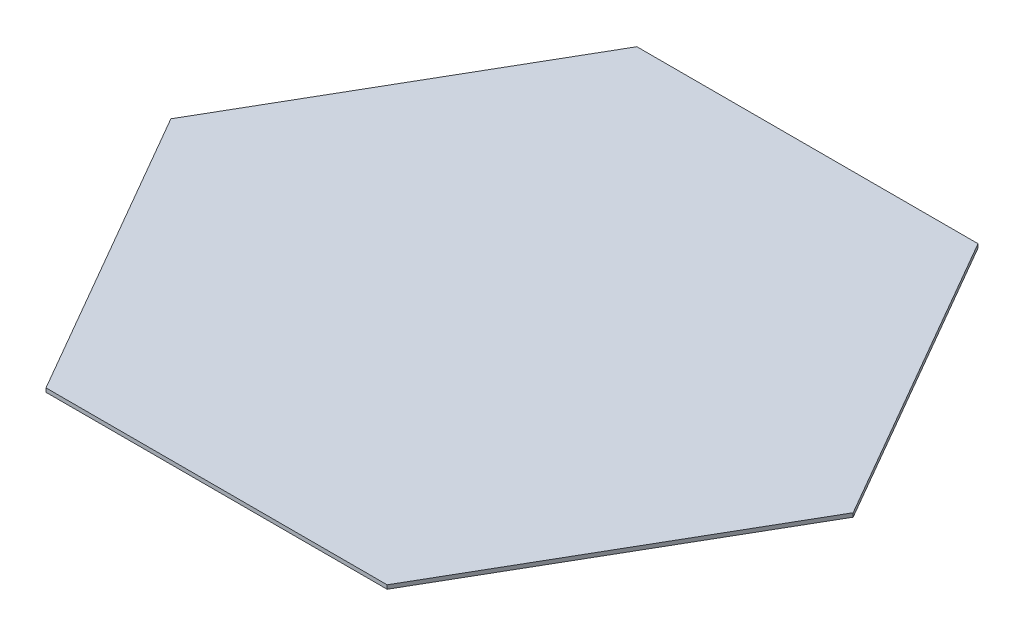
SolidWorks part; units mm, degrees
material "1.0037 (S235JR)"
ref_plane "Plan de face" through (0, 0, 0) normal (0, 0, 1) x (1, 0, 0)
ref_plane "Plan de dessus" through (0, 0, 0) normal (0, 1, 0) x (1, 0, 0)
ref_plane "Plan de droite" through (0, 0, 0) normal (1, 0, 0) x (0, 0, -1)
sketch "Esquisse1" plane through (0, 0, 0) normal (0, 1, 0) x (1, 0, 0)
  line L1 (220, 381.0512) -> (-220, 381.0512)
  line L2 (-220, 381.0512) -> (-440, 0)
  line L3 (-440, 0) -> (-220, -381.0512)
  line L4 (-220, -381.0512) -> (220, -381.0512)
  line L5 (220, -381.0512) -> (440, 0)
  line L6 (440, 0) -> (220, 381.0512)
  circle A0 centre (0, 0) radius 381.0512 construction
  dimension "D1" = 880
extrude "Boss.-Extru.1" add sketch "Esquisse1" along normal blind 5
